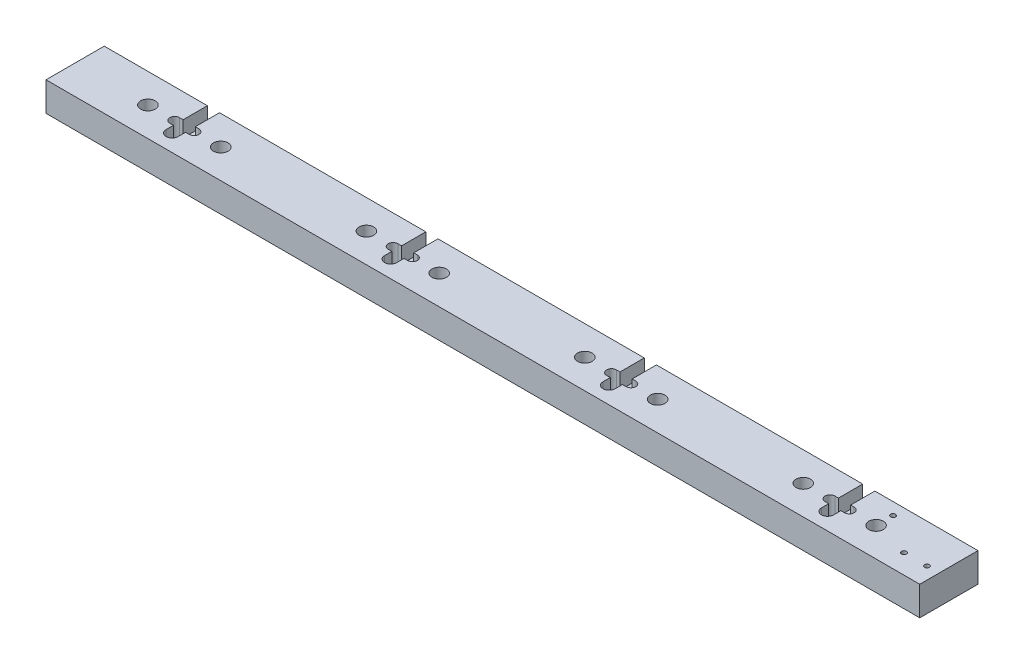
SolidWorks part; units mm, degrees
material "HDPE-green"
ref_plane "Front Plane" through (0, 0, 0) normal (0, 0, 1) x (1, 0, 0)
ref_plane "Top Plane" through (0, 0, 0) normal (0, 1, 0) x (1, 0, 0)
ref_plane "Right Plane" through (0, 0, 0) normal (1, 0, 0) x (0, 0, -1)
sketch "Sketch1" plane through (0, 0, 0) normal (0, 1, 0) x (1, 0, 0)
  line L1 (-180, -12) -> (180, -12)
  line L2 (-180, -12) -> (-180, 12)
  line L3 (-180, 12) -> (180, 12)
  line L4 (180, -12) -> (180, 12)
  line L5 (-180, -12) -> (180, 12) construction
  line L6 (-180, 12) -> (180, -12) construction
  point P0 (0, 0)
  dimension "D1" = 24
  dimension "D2" = 360
extrude "Boss-Extrude1" add sketch "Sketch1" along normal blind 12
sketch "Sketch2" plane through (0, 12, 0) normal (0, 1, 0) x (1, 0, 0)
  line L0 (-180, 12) -> (-180, -12) construction
  circle A0 centre (-150, 0) radius 3
  circle A1 centre (-120, 0) radius 3
  dimension "D1" = 6
  dimension "D3" = 6
  dimension "D2" = 30
  dimension "D4" = 60
extrude "Cut-Extrude1" cut sketch "Sketch2" against normal up to next
sketch "Sketch11" plane through (-63.4848, 12, 93.4814) normal (0, 1, 0) x (-1, 0, 0)
  line L0 (67.5152, -93.4814) -> (75.5152, -93.4814) construction
  line L1 (67.5152, -91.4814) -> (75.5152, -91.4814)
  line L2 (67.5152, -95.4814) -> (75.5152, -95.4814)
  line L3 (-243.4848, -105.4814) -> (116.5152, -105.4814) construction
  arc A0 (67.5152, -91.4814) -> (67.5152, -95.4814) centre (67.5152, -93.4814) ccw
  arc A1 (75.5152, -95.4814) -> (75.5152, -91.4814) centre (75.5152, -93.4814) ccw
  point P2 (71.5152, -93.4814)
  dimension "D1" = 8
  dimension "D2" = 2
  dimension "D4" = 135
  dimension "D3" = 12
extrude "Cut-Extrude2" cut sketch "Sketch11" against normal blind 8
sketch "Sketch13" plane through (-63.4848, 12, 93.4814) normal (0, 1, 0) x (-1, 0, 0)
  line L0 (71.5152, -88.4814) -> (71.5152, -142.1112) construction
  line L1 (74.0152, -88.4814) -> (74.0152, -142.1112)
  line L2 (69.0152, -88.4814) -> (69.0152, -142.1112)
  line L3 (-243.4848, -105.4814) -> (116.5152, -105.4814) construction
  arc A0 (74.0152, -88.4814) -> (69.0152, -88.4814) centre (71.5152, -88.4814) ccw
  arc A1 (69.0152, -142.1112) -> (74.0152, -142.1112) centre (71.5152, -142.1112) ccw
  point P2 (71.5152, -115.2963)
  dimension "D1" = 17
  dimension "D2" = 2.5
  dimension "D3" = 135
extrude "Cut-Extrude3" cut sketch "Sketch13" against normal blind 6.5
pattern_linear "LPattern1" count 4 spacing 90 along (1, 0, 0) of "Cut-Extrude1", "Cut-Extrude2", "Cut-Extrude3"
hole_wizard "Ø2.0 (2) Diameter Hole1" positions "Sketch5" profile "Sketch4" hole size "Ø2.0" standard "ISO" end condition up to next
sketch "Sketch5" plane through (0, 0, 0) normal (0, -1, 0) x (1, 0, 0)
  line L0 (-180, 12) -> (180, 12) construction
  line L3 (-180, 12) -> (180, 12) construction
  line L4 (180, 12) -> (180, -12) construction
  point P0 (165.5, 4)
  point P1 (175, 4)
  point P9 (150, -7)
  dimension "D1" = 8
  dimension "D2" = 8
  dimension "D3" = 5
  dimension "D4" = 9.5
  dimension "D5" = 30
  dimension "D6" = 19
sketch "Sketch4" plane through (165.5, 0, 4) normal (1, 0, 0) x (0, 0, -1)
  line L0 (0, 0) -> (0, 12)
  line L1 (0, 12) -> (1, 12)
  line L2 (1, 12) -> (1, 0)
  line L5 (1, 0) -> (0, 0)
  line L11 (0, -6.35) -> (0, 107.95) construction
  dimension "Thru Hole Dia." = 2
  dimension "Thru Hole Depth" = 12
